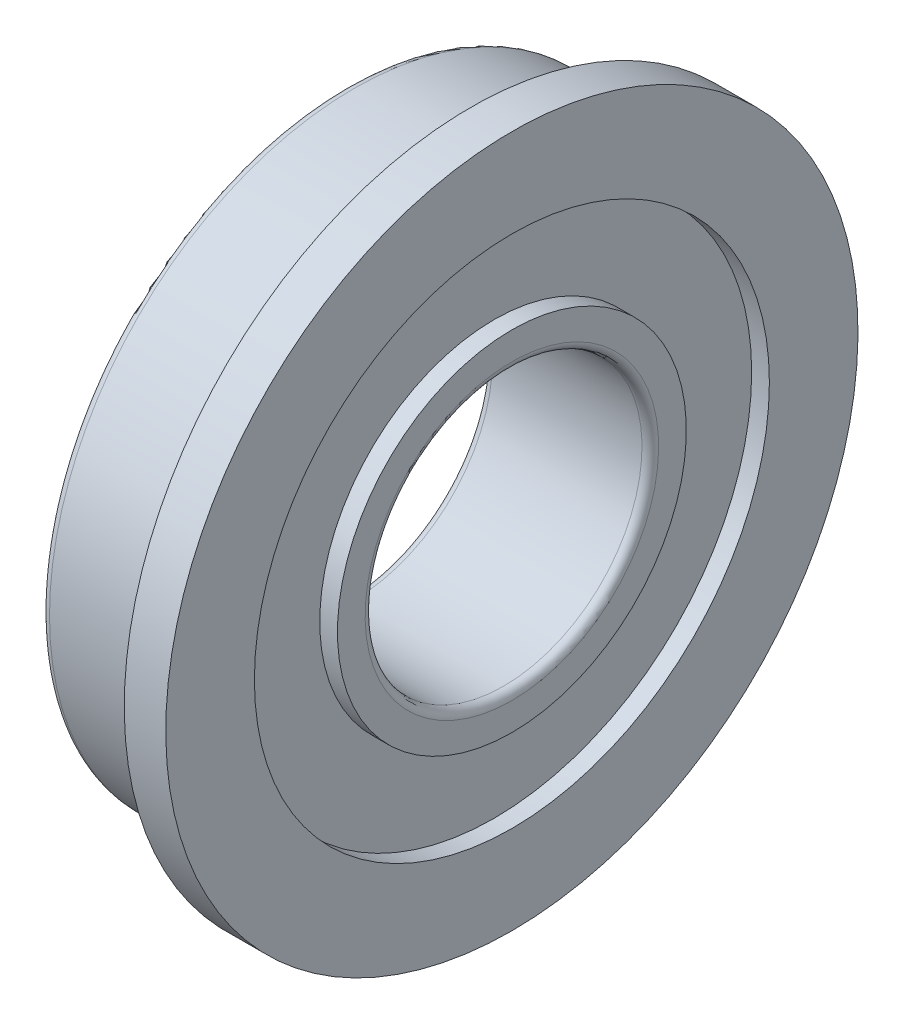
SolidWorks part; units mm, degrees
ref_plane "Front Plane" through (0, 0, 0) normal (0, 0, 1) x (1, 0, 0)
ref_plane "Top Plane" through (0, 0, 0) normal (0, 1, 0) x (1, 0, 0)
ref_plane "Right Plane" through (0, 0, 0) normal (1, 0, 0) x (0, 0, -1)
sketch "Sketch1" plane through (0, 0, 0) normal (0, 0, 1) x (1, 0, 0)
  line L0 (-4.5, 0) -> (1.5, 0) construction
  line L1 (0, 11.2) -> (0, 12.5)
  line L2 (0, 12.5) -> (1.5, 12.5)
  line L3 (1.5, 12.5) -> (1.5, 9.3)
  line L4 (1.5, 5) -> (-4.5, 5)
  line L5 (-4.5, 5) -> (-4.5, 6.3)
  line L6 (-4.5, 11) -> (-0.2, 11)
  line L7 (-4.5, 9.3) -> (-3.86, 9.3)
  line L8 (-3.86, 9.3) -> (-3.86, 6.3)
  line L9 (-3.86, 6.3) -> (-4.5, 6.3)
  line L10 (1.5, 9.3) -> (0.86, 9.3)
  line L11 (0.86, 9.3) -> (0.86, 6.3)
  line L12 (0.86, 6.3) -> (1.5, 6.3)
  line L13 (-4.5, 9.3) -> (-4.5, 11)
  line L14 (1.5, 6.3) -> (1.5, 5)
  arc A0 (-0.2, 11) -> (0, 11.2) centre (0, 11) ccw
  dimension "FIX_1" = 0.2
  dimension "D_s" = 10
  dimension "C" = 1.5
  dimension "MSM_2" = 12.6
  dimension "MSM_1" = 18.6
  dimension "D" = 22
  dimension "D1." = 25
  dimension "B" = 6
  dimension "MSM_3" = 0.64
revolve "Revolve1" add sketch "Sketch1" angle 360 about L0
fillet "Fillet1" radius 0.3 3 edges at (1.5, -5, 0) (-4.5, -5, 0) (-4.5, -11, 0)
